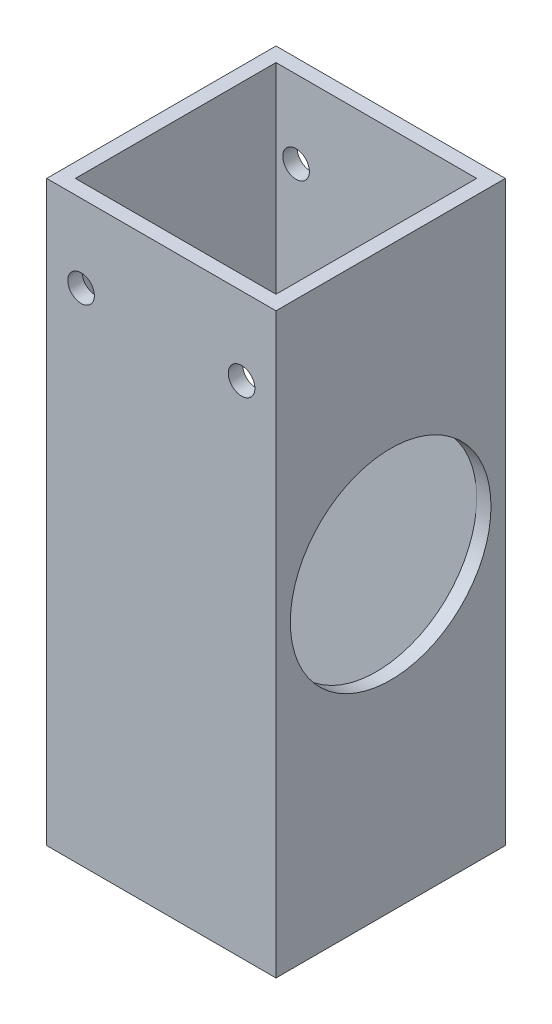
SolidWorks part; units mm, degrees
ref_plane "Front Plane" through (0, 0, 0) normal (0, 0, 1) x (1, 0, 0)
ref_plane "Top Plane" through (0, 0, 0) normal (0, 1, 0) x (1, 0, 0)
ref_plane "Right Plane" through (0, 0, 0) normal (1, 0, 0) x (0, 0, -1)
sketch "Sketch1" plane through (0, 0, 0) normal (0, 1, 0) x (1, 0, 0)
  line L0 (11.1125, 11.1125) -> (-11.1125, 11.1125)
  line L1 (12.7, 12.7) -> (-12.7, 12.7)
  line L2 (-12.7, 12.7) -> (-12.7, -12.7)
  line L3 (-12.7, -12.7) -> (12.7, -12.7)
  line L4 (12.7, -12.7) -> (12.7, 12.7)
  line L5 (-11.1125, 11.1125) -> (-11.1125, -11.1125)
  line L6 (-11.1125, -11.1125) -> (11.1125, -11.1125)
  line L7 (11.1125, -11.1125) -> (11.1125, 11.1125)
  circle A0 centre (0, 0) radius 12.7 construction
  circle A1 centre (0, 0) radius 11.1125 construction
  dimension "D1" = 25.4
  dimension "D2" = 1.5875
extrude "Boss-Extrude1" add sketch "Sketch1" along normal up to vertex (63.999 mm away)
sketch "Sketch3" plane through (12.7, 0, 0) normal (1, 0, 0) x (0, 0, -1)
  line L0 (0, 63.999) -> (0, 0) construction
  circle A0 centre (0, 33.3375) radius 11.1125
  dimension "D1" = 22.225
  dimension "D2" = 33.3375
extrude "Cut-Extrude2" cut sketch "Sketch3" against normal through all
sketch "Sketch4" plane through (12.7, 0, 0) normal (1, 0, 0) x (0, 0, -1)
  line L0 (0, 63.999) -> (0, 0) construction
sketch3d "3DSketch3"
  line L0 (38.1087, 33.3375, 0) -> (-28.5664, 33.3375, 0) construction
  line L1 (12.7, 63.999, 0) -> (12.7, 0, 0) construction
  line L2 (12.7, 0, 12.7) -> (12.7, 0, -12.7) construction
  line L3 (-12.7, 63.999, 0) -> (12.7, 63.999, 0) construction
  point P0 (38.1087, 33.3375, 0)
  point P1 (-28.5664, 33.3375, 0)
sketch "Sketch5" plane through (0, 0, 0) normal (0, 0, 1) x (1, 0, 0)
  line L0 (0, 0) -> (0, 63.999) construction
  line L1 (-12.7, 63.999) -> (12.7, 63.999) construction
sketch "Sketch6" plane through (0, 0, -12.7) normal (0, 0, -1) x (-1, 0, 0)
  circle A0 centre (8.8899, 55.381) radius 1.4732
  dimension "D1" = 2.9464
extrude "Cut-Extrude3" cut sketch "Sketch6" against normal through all both and the other way through all
sketch "Sketch7" plane through (0, 0, -12.7) normal (0, 0, -1) x (-1, 0, 0)
  circle A0 centre (-8.8899, 55.381) radius 1.4732
  dimension "D1" = 2.9464
extrude "Cut-Extrude4" cut sketch "Sketch7" against normal through all both and the other way through all
equation "\"diameter\"=0.875"
equation "\"D1@Sketch3\"=\"diameter\""
equation "\"D2@Sketch3\"=\"diameter\"*1.5"
equation "\"D1\"= 2 * \"diameter\" + 1.03 + .5 -  ( \"diameter\" - .5 )  / 2"
